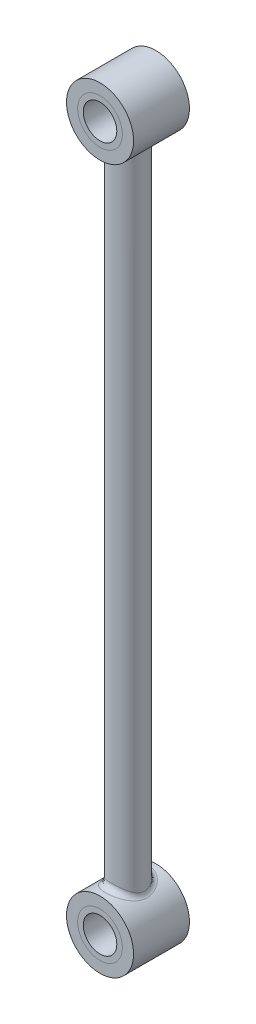
SolidWorks part; units mm, degrees
ref_plane "Front Plane" through (0, 0, 0) normal (0, 0, 1) x (1, 0, 0)
ref_plane "Top Plane" through (0, 0, 0) normal (0, 1, 0) x (1, 0, 0)
ref_plane "Right Plane" through (0, 0, 0) normal (1, 0, 0) x (0, 0, -1)
sketch "Sketch1" plane through (0, 0, 0) normal (0, 1, 0) x (1, 0, 0)
  circle A0 centre (0, 0) radius 3
  dimension "D1" = 6
extrude "Boss-Extrude1" add sketch "Sketch1" along normal mid plane 116
sketch "Sketch2" plane through (0, 0, 0) normal (0, 0, 1) x (1, 0, 0)
  circle A1 centre (0, -63) radius 6
  circle A3 centre (0, -63) radius 4
  circle A4 centre (0, 63) radius 6
  circle A5 centre (0, 63) radius 4
  dimension "D1" = 63
  dimension "D2" = 12
  dimension "D3" = 12
  dimension "D5" = 8
  dimension "D6" = 8
  dimension "D4" = 63
extrude "Boss-Extrude2" add sketch "Sketch2" along normal mid plane 10
sketch "Sketch3" plane through (0, 0, 0) normal (0, 0, 1) x (1, 0, 0)
  circle A2 centre (0, -63) radius 4
  circle A3 centre (0, -63) radius 3
  circle A4 centre (0, 63) radius 3
  circle A5 centre (0, 63) radius 4
  dimension "D1" = 8
  dimension "D2" = 6
  dimension "D3" = 6
  dimension "D4" = 8
extrude "Boss-Extrude3" add sketch "Sketch3" along normal mid plane 10 separate body
fillet "Fillet1" radius 1 1 edges at (-0.3027, -57.0076, 2.9847)
